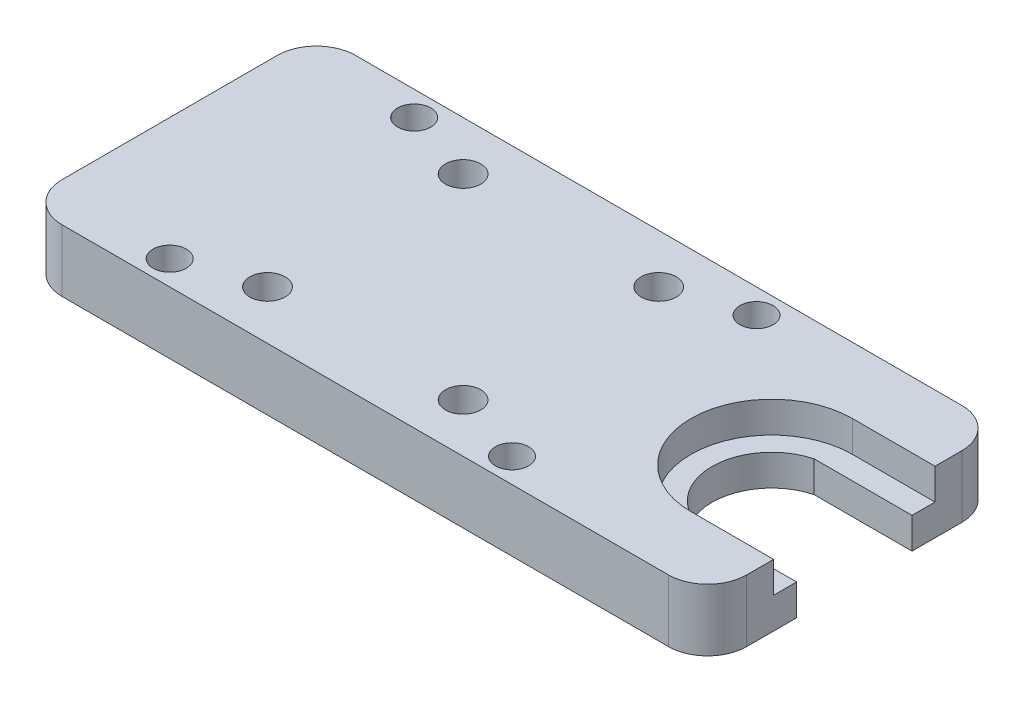
SolidWorks part; units mm, degrees
ref_plane "Front Plane" through (0, 0, 0) normal (0, 0, 1) x (1, 0, 0)
ref_plane "Top Plane" through (0, 0, 0) normal (0, 1, 0) x (1, 0, 0)
ref_plane "Right Plane" through (0, 0, 0) normal (1, 0, 0) x (0, 0, -1)
ref_plane "Plane1" through (0, 0, 0) normal (0, -1, 0) x (1, 0, 0)
sketch "Sketch1" plane through (0, 0, 0) normal (0, -1, 0) x (1, 0, 0)
  line L0 (-41.5, 3) -> (28.5, 3)
  line L1 (28.5, 3) -> (28.5, 33)
  line L2 (28.5, 33) -> (-41.5, 33)
  line L3 (-41.5, 33) -> (-41.5, 3)
  dimension "D4" = 70
  dimension "D6" = 30
extrude "Boss-Extrude1" add sketch "Sketch1" against normal blind 6.35
sketch "Sketch9" plane through (0, 6.35, 0) normal (0, 1, 0) x (1, 0, 0)
  line L0 (28.5, -18) -> (13.9492, -18) construction
  line L1 (28.5, -3) -> (28.5, -33) construction
  line L2 (28.5, -12.1) -> (18.5, -12.1)
  line L3 (28.5, -23.9) -> (18.5, -23.9)
  line L4 (28.5, -12.1) -> (28.5, -23.9)
  arc A0 (18.5, -12.1) -> (18.5, -23.9) centre (20.0492, -18) ccw
  dimension "D2" = 6.1
  dimension "D1" = 11.8
  dimension "D3" = 10
extrude "Cut-Extrude1" cut sketch "Sketch9" against normal through all
sketch "Sketch10" plane through (0, 6.35, 0) normal (0, 1, 0) x (1, 0, 0)
  line L0 (28.5, -33) -> (28.5, -3) construction
  line L1 (28.5, -18) -> (11.5984, -18) construction
  line L2 (28.5, -26.25) -> (20.0492, -26.25)
  line L3 (28.5, -9.75) -> (20.0492, -9.75)
  line L4 (28.5, -9.75) -> (28.5, -26.25)
  arc A0 (20.0492, -26.25) -> (20.0492, -9.75) centre (20.0492, -18) cw
  point P11 (20.0492, -18)
  dimension "D1" = 16.5
extrude "Cut-Extrude2" cut sketch "Sketch10" against normal up to vertex (3.175 mm away)
hole_wizard "M3 Clearance Hole2" positions "3DSketch1" profile "Sketch11" hole size "M3" standard "ANSI Metric"
sketch3d "3DSketch1"
  line L0 (-21.5, 6.35, 8) -> (-1.5, 6.35, 8) construction
  line L1 (-1.5, 6.35, 8) -> (-1.5, 6.35, 28) construction
  line L2 (-1.5, 6.35, 28) -> (-21.5, 6.35, 28) construction
  line L3 (-21.5, 6.35, 28) -> (-21.5, 6.35, 8) construction
  line L4 (-41.5, 6.35, 18) -> (28.2992, 6.35, 18) construction
  line L5 (-41.5, 6.35, 33) -> (-41.5, 6.35, 3) construction
  arc A0 (20.0492, 6.35, 9.75) -> (20.0492, 6.35, 26.25) centre (20.0492, 6.35, 18) ccw construction
  point P0 (-21.5, 6.35, 28)
  point P2 (-21.5, 6.35, 8)
  point P4 (-1.5, 6.35, 8)
  point P6 (-1.5, 6.35, 28)
  point P21 (20.0492, 14.6, 18)
  point P23 (-21.5, 6.35, 18)
  dimension "D1" = 20
  dimension "D2" = 20
  dimension "D3" = 20
sketch "Sketch11" plane through (-21.5, 6.35, 28) normal (1, 0, 0) x (0, 0, 1)
  line L0 (0, 0) -> (0, 6.35)
  line L1 (0, 6.35) -> (1.8, 6.35)
  line L2 (1.8, 6.35) -> (1.8, 0)
  line L5 (1.8, 0) -> (0, 0)
  line L11 (0, -6.35) -> (0, 107.95) construction
  dimension "Thru Hole Dia." = 3.6
  dimension "Thru Hole Depth" = 6.35
fillet "Fillet1" radius 4 4 edges at (-41.5, 3.175, 3) (-41.5, 3.175, 33) (28.5, 3.175, 33) (28.5, 3.175, 3)
hole_wizard "M3 Clearance Hole3" positions "3DSketch2" profile "Sketch12" hole size "M3" standard "ANSI Metric"
sketch3d "3DSketch2"
  line L0 (-29, 6.35, 5.5) -> (6, 6.35, 5.5)
  line L1 (6, 6.35, 5.5) -> (6, 6.35, 30.5)
  line L2 (6, 6.35, 30.5) -> (-29, 6.35, 30.5)
  line L3 (-29, 6.35, 30.5) -> (-29, 6.35, 5.5)
  line L5 (-21.5, 6.35, 8) -> (-21.5, 6.35, 28)
  line L6 (-21.5, 0, 8) -> (-21.5, 6.35, 8) construction
  line L7 (-21.5, 0, 28) -> (-21.5, 6.35, 28) construction
  circle A0 centre (-1.5, 6.35, 8) radius 1.8 construction
  point P2 (-29, 6.35, 5.5)
  point P4 (-29, 6.35, 30.5)
  point P6 (6, 6.35, 30.5)
  point P8 (6, 6.35, 5.5)
  point P25 (-21.5, 6.35, 18)
  point P26 (-29, 6.35, 18)
  point P32 (-1.5, 8.15, 8)
  dimension "D1" = 7.5
  dimension "D2" = 7.5
  dimension "D3" = 2.5
sketch "Sketch12" plane through (-29, 6.35, 5.5) normal (1, 0, 0) x (0, 0, 1)
  line L0 (0, 0) -> (0, 6.35)
  line L1 (0, 6.35) -> (1.7, 6.35)
  line L2 (1.7, 6.35) -> (1.7, 0)
  line L5 (1.7, 0) -> (0, 0)
  line L11 (0, -6.35) -> (0, 107.95) construction
  dimension "Thru Hole Dia." = 3.4
  dimension "Thru Hole Depth" = 6.35
equation "\"D3\"=0.393701"
